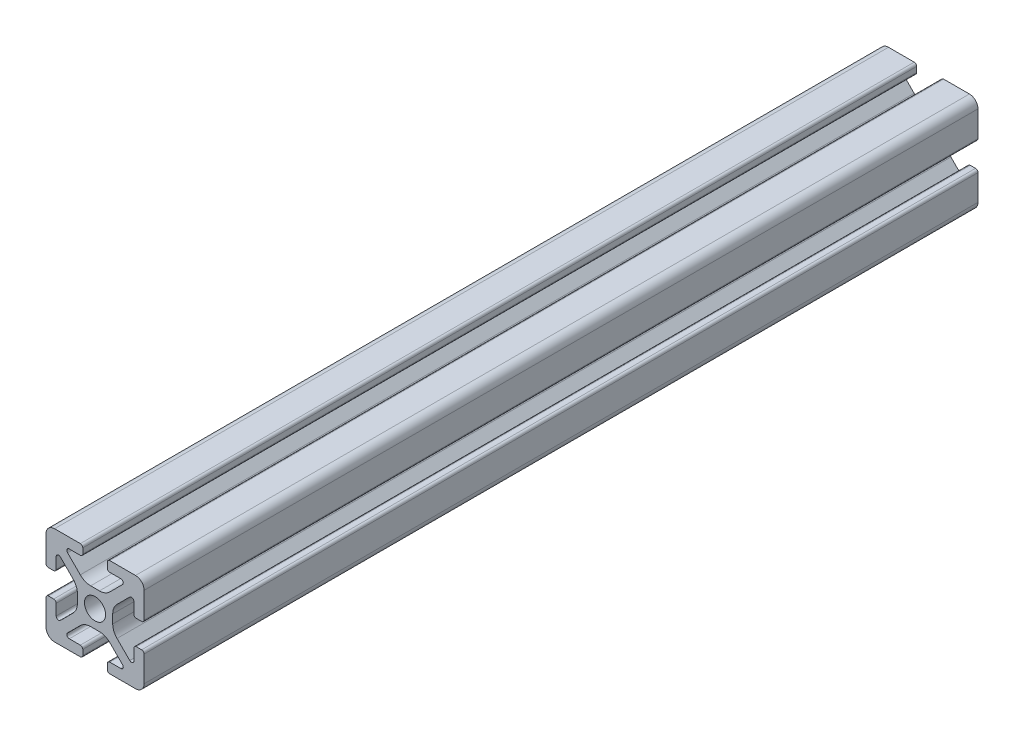
SolidWorks part; units mm, degrees
material "6063-T6"
ref_plane "Front Plane" through (0, 0, 0) normal (0, 0, 1) x (1, 0, 0)
ref_plane "Top Plane" through (0, 0, 0) normal (0, 1, 0) x (1, 0, 0)
ref_plane "Right Plane" through (0, 0, 0) normal (1, 0, 0) x (0, 0, -1)
sketch "Sketch2" plane through (0, 0, 0) normal (0, 0, 1) x (1, 0, 0)
  line L0 (0, 10) -> (0, -10) construction
  line L1 (-10, 0) -> (10, 0) construction
  line L2 (2.5, -10) -> (10, -10)
  line L3 (10, -10) -> (10, -2.5)
  line L4 (2.5, -10) -> (2.5, -7.9246)
  line L5 (2.5, -7.9246) -> (6.4571, -7.9246)
  line L6 (6.4571, -7.9246) -> (2.1325, -3.6)
  line L7 (0, 0) -> (10, -10) construction
  line L8 (10, -2.5) -> (7.9246, -2.5)
  line L9 (7.9246, -2.5) -> (7.9246, -6.4571)
  line L10 (7.9246, -6.4571) -> (3.6, -2.1325)
  line L11 (5.7623, -4.2948) -> (4.2948, -5.7623) construction
  circle A0 centre (0, 0) radius 2.15
  arc A1 (5.25, -7.9246) -> (5.6036, -7.0711) centre (5.25, -7.4246) ccw construction
  point P8 (0, -3.6)
  point P16 (5.0286, -5.0286)
  dimension "Center Hole Diameter" = 4.3
  dimension "D3" = 0.5
  dimension "Rail Height" = 20
  dimension "Rail Width" = 20
  dimension "T-Slot Width" = 5
  dimension "Slot Depth" = 6.4
  dimension "Slot Inner Width" = 11.5
sketch "Sketch3" plane through (0, 0, 0) normal (1, 0, 0) x (0, 0, -1)
  line L0 (-85, -10) -> (85, -10) construction
  line L1 (-59.6, 0) -> (59.6, 0) construction
  line L2 (0, 10) -> (0, -10) construction
  line L3 (0, 10) -> (0, -10) construction
  point P6 (-59.6, 0)
  point P8 (59.6, 0)
  dimension "Length" = 170
  dimension "D1" = 25.4
sketch "Sketch4" plane through (0, 0, 0) normal (0, 0, 1) x (1, 0, 0)
  line L0 (3, -10) -> (8.25, -10)
  line L1 (2.5, -10) -> (10, -10) construction
  line L2 (2.5, -10) -> (2.5, -7.9246) construction
  line L3 (2.5, -7.9246) -> (6.4571, -7.9246) construction
  line L4 (2.5, -8.4246) -> (2.5, -9.5)
  line L5 (3, -7.9246) -> (5.25, -7.9246)
  line L6 (0, -3.6) -> (0.8898, -3.6)
  line L7 (6.4571, -7.9246) -> (2.1325, -3.6) construction
  line L8 (3.0112, -4.4787) -> (5.6036, -7.0711)
  line L9 (10, -10) -> (10, -2.5) construction
  line L10 (7.9246, -6.4571) -> (3.6, -2.1325) construction
  line L11 (7.9246, -2.5) -> (7.9246, -6.4571) construction
  line L12 (7.9246, -5.25) -> (7.9246, -3)
  line L13 (10, -2.5) -> (7.9246, -2.5) construction
  line L14 (8.4246, -2.5) -> (9.5, -2.5)
  line L15 (10, -3) -> (10, -8.25)
  line L16 (7.0711, -5.6036) -> (4.4787, -3.0112)
  line L17 (3.6, 0) -> (3.6, -0.8898)
  line L18 (-10, 0) -> (10, 0) construction
  line L19 (0, -3.6) -> (0, -2.15)
  line L20 (0, 10) -> (0, -10) construction
  line L21 (3.6, 0) -> (2.15, 0)
  arc A0 (2.5, -9.5) -> (3, -10) centre (3, -9.5) ccw
  arc A1 (5.25, -7.9246) -> (5.6036, -7.0711) centre (5.25, -7.4246) ccw construction
  arc A2 (2.5, -8.4246) -> (3, -7.9246) centre (3, -8.4246) cw
  arc A3 (5.25, -7.9246) -> (5.6036, -7.0711) centre (5.25, -7.4246) ccw
  arc A4 (0.8898, -3.6) -> (3.0112, -4.4787) centre (0.8898, -6.6) cw
  arc A5 (8.25, -10) -> (10, -8.25) centre (8.25, -8.25) ccw
  arc A6 (7.0711, -5.6036) -> (7.9246, -5.25) centre (7.4246, -5.25) ccw
  arc A7 (7.9246, -3) -> (8.4246, -2.5) centre (8.4246, -3) cw
  arc A8 (9.5, -2.5) -> (10, -3) centre (9.5, -3) cw
  arc A9 (4.4787, -3.0112) -> (3.6, -0.8898) centre (6.6, -0.8898) cw
  circle A10 centre (0, 0) radius 2.15 construction
  arc A11 (0, -2.15) -> (2.15, 0) centre (0, 0) ccw
  dimension "D1" = 1.75
  dimension "D2" = 3
extrude "Boss-Extrude1" add sketch "Sketch4" along normal mid plane 170
mirror "Mirror1" about plane through (0, 0, 0) normal (1, 0, 0) of bodies 134
mirror "Mirror2" about plane through (0, 0, 0) normal (0, 1, 0) of bodies 135
equation "\"D3@Sketch2\"=\"T-Slot Width@Sketch2\"*0.1"
equation "\"D1@Sketch4\"=\"D3@Sketch2\"*3.5"
equation "\"D2@Sketch4\"=\"D3@Sketch2\"*6"
equation "\"D1@Boss-Extrude1\"=\"Length@Sketch3\""
